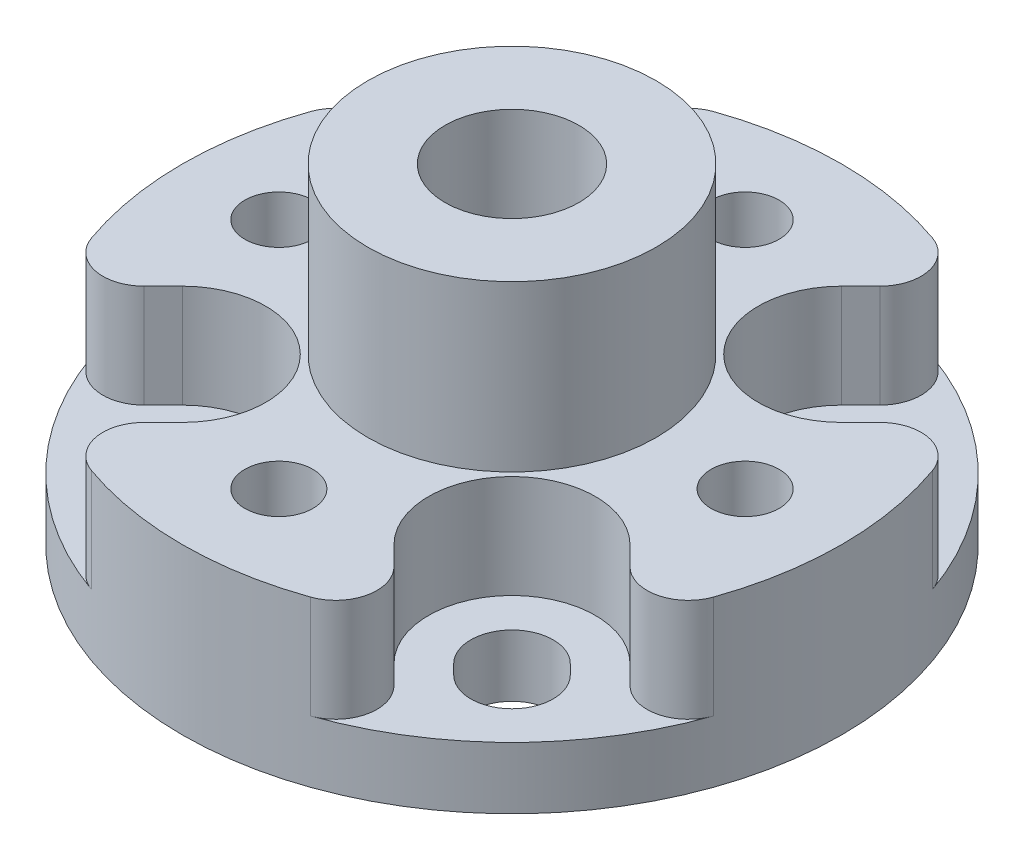
SolidWorks part; units mm, degrees
material "Brass"
ref_plane "前视基准面" through (0, 0, 0) normal (0, 0, 1) x (1, 0, 0)
ref_plane "上视基准面" through (0, 0, 0) normal (0, 1, 0) x (1, 0, 0)
ref_plane "右视基准面" through (0, 0, 0) normal (1, 0, 0) x (0, 0, -1)
sketch "Sketch1" plane through (0, 0, 0) normal (0, 1, 0) x (1, 0, 0)
  circle A0 centre (0, 0) radius 16
  dimension "D1" = 32
extrude "Boss-Extrude1" add sketch "Sketch1" along normal blind 8
sketch "Sketch2" plane through (0, 8, 0) normal (0, 1, 0) x (1, 0, 0)
  circle A0 centre (0, 0) radius 7
  dimension "D1" = 14
extrude "Boss-Extrude2" add sketch "Sketch2" along normal blind 8
sketch "Sketch3" plane through (0, 16, 0) normal (0, 1, 0) x (1, 0, 0)
  circle A0 centre (0, 0) radius 3.25
  dimension "D1" = 6.5
extrude "Cut-Extrude1" cut sketch "Sketch3" against normal through all
cosmetic thread "Cosmetic Thread1" parameters "D2"=8
sketch "Sketch4" plane through (0, 8, 0) normal (0, 1, 0) x (1, 0, 0)
  line L0 (-25.1061, 0) -> (26.0873, 0) construction
  line L1 (11.3137, 0) -> (0, 11.3137) construction
  line L2 (0, 11.3137) -> (-11.3137, 0) construction
  line L3 (-11.3137, 0) -> (0, -11.3137) construction
  line L4 (0, -11.3137) -> (11.3137, 0) construction
  circle A0 centre (0, 0) radius 8 construction
  circle A2 centre (0, 11.3137) radius 1.65
  circle A4 centre (-11.3137, 0) radius 1.65
  circle A5 centre (0, -11.3137) radius 1.65
  circle A6 centre (11.3137, 0) radius 1.65
  dimension "D1" = 16
  dimension "D2" = 3.3
  dimension "D3" = 3.3
  dimension "D4" = 3.3
  dimension "D5" = 3.3
extrude "Cut-Extrude2" cut sketch "Sketch4" against normal through all
cosmetic thread "Cosmetic Thread2" parameters "D2"=4
cosmetic thread "Cosmetic Thread3" parameters "D2"=4
cosmetic thread "Cosmetic Thread4" parameters "D2"=4
cosmetic thread "Cosmetic Thread5" parameters "D2"=4
sketch "Sketch5" plane through (0, 8, 0) normal (0, 1, 0) x (1, 0, 0)
  line L0 (0, 16.4633) -> (0, -18.0216) construction
  line L1 (-14.3574, 14.3574) -> (0, 0) construction
  line L2 (-8, 8) -> (-8.4853, 8.4853) construction
  line L7 (-9.4142, 6.5858) -> (-9.8995, 7.0711)
  line L8 (-6.5858, 9.4142) -> (-7.0711, 9.8995)
  line L9 (0, 0) -> (13.3651, 13.3651) construction
  line L10 (8, -8) -> (8.4853, -8.4853) construction
  line L11 (6.5858, -9.4142) -> (7.0711, -9.8995)
  line L12 (9.4142, -6.5858) -> (9.8995, -7.0711)
  line L13 (-23.0915, 0) -> (18.9541, 0) construction
  line L14 (8, 8) -> (8.4853, 8.4853) construction
  line L15 (6.5858, 9.4142) -> (7.0711, 9.8995)
  line L16 (9.4142, 6.5858) -> (9.8995, 7.0711)
  line L17 (-8, -8) -> (-8.4853, -8.4853) construction
  line L18 (-9.4142, -6.5858) -> (-9.8995, -7.0711)
  line L19 (-6.5858, -9.4142) -> (-7.0711, -9.8995)
  arc A0 (6.5858, 9.4142) -> (9.4142, 6.5858) centre (8, 8) ccw
  arc A1 (-9.4142, 6.5858) -> (-6.5858, 9.4142) centre (-8, 8) ccw
  arc A2 (-7.0711, 9.8995) -> (-9.8995, 7.0711) centre (-8.4853, 8.4853) ccw
  arc A3 (6.5858, -9.4142) -> (9.4142, -6.5858) centre (8, -8) cw
  arc A4 (9.8995, -7.0711) -> (7.0711, -9.8995) centre (8.4853, -8.4853) cw
  arc A5 (9.8995, 7.0711) -> (7.0711, 9.8995) centre (8.4853, 8.4853) ccw
  arc A6 (-9.4142, -6.5858) -> (-6.5858, -9.4142) centre (-8, -8) cw
  arc A7 (-7.0711, -9.8995) -> (-9.8995, -7.0711) centre (-8.4853, -8.4853) cw
  point P5 (-8.2426, 8.2426)
  point P18 (8.2426, -8.2426)
  point P25 (8.2426, 8.2426)
  point P34 (-8.2426, -8.2426)
  point P39 (0, 0)
  dimension "D2" = 8
  dimension "D3" = 2
  dimension "D1" = 45
  dimension "D4" = 90
  dimension "D5" = 24
  dimension "D6" = 2
extrude "Cut-Extrude3" cut sketch "Sketch5" against normal through all
sketch "Sketch6" plane through (0, 8, 0) normal (0, 1, 0) x (1, 0, 0)
  line L0 (0, 16.4633) -> (0, -18.1659) construction
  line L1 (-20.1715, 0) -> (22.2492, 0) construction
  line L2 (0, 0) -> (-13.628, 13.628) construction
  line L3 (-10.8638, 5.1362) -> (-11.7912, 6.0636)
  line L4 (5.1362, 10.8638) -> (6.0636, 11.7912)
  line L5 (-5.1362, 10.8638) -> (-6.0636, 11.7912)
  line L6 (10.8638, 5.1362) -> (11.7912, 6.0636)
  line L7 (10.8638, -5.1362) -> (11.7912, -6.0636)
  line L8 (5.1362, -10.8638) -> (6.0636, -11.7912)
  line L9 (-5.1362, -10.8638) -> (-6.0636, -11.7912)
  line L10 (-10.8638, -5.1362) -> (-11.7912, -6.0636)
  arc A0 (-10.8638, 5.1362) -> (-5.1362, 10.8638) centre (-8, 8) ccw
  arc A2 (-15.0919, 5.3136) -> (-11.7912, 6.0636) centre (-13.2054, 4.6494) cw
  arc A3 (-5.3136, 15.0919) -> (-6.0636, 11.7912) centre (-4.6494, 13.2054) ccw
  arc A5 (-5.3136, 15.0919) -> (-15.0919, 5.3136) centre (0, 0) ccw
  arc A6 (5.3136, 15.0919) -> (6.0636, 11.7912) centre (4.6494, 13.2054) cw
  arc A7 (5.1362, 10.8638) -> (10.8638, 5.1362) centre (8, 8) ccw
  arc A8 (15.0919, 5.3136) -> (11.7912, 6.0636) centre (13.2054, 4.6494) ccw
  arc A9 (15.0919, 5.3136) -> (5.3136, 15.0919) centre (0, 0) ccw
  arc A10 (15.0919, -5.3136) -> (11.7912, -6.0636) centre (13.2054, -4.6494) cw
  arc A11 (10.8638, -5.1362) -> (5.1362, -10.8638) centre (8, -8) ccw
  arc A12 (5.3136, -15.0919) -> (6.0636, -11.7912) centre (4.6494, -13.2054) ccw
  arc A13 (5.3136, -15.0919) -> (15.0919, -5.3136) centre (0, 0) ccw
  arc A14 (-5.3136, -15.0919) -> (-6.0636, -11.7912) centre (-4.6494, -13.2054) cw
  arc A15 (-5.1362, -10.8638) -> (-10.8638, -5.1362) centre (-8, -8) ccw
  arc A16 (-15.0919, -5.3136) -> (-11.7912, -6.0636) centre (-13.2054, -4.6494) ccw
  arc A17 (-15.0919, -5.3136) -> (-5.3136, -15.0919) centre (0, 0) ccw
  point P11 (2.8638, 2.8638)
  point P13 (-10.7642, 16.4918)
  point P14 (-2.8638, -2.8638)
  point P15 (-16.4918, 10.7642)
  point P52 (0, 0)
  dimension "D1" = 8.1
  dimension "D2" = 16
  dimension "D4" = 2
  dimension "D3" = 45
  dimension "D5" = 4.05
  dimension "D6" = 4.05
  dimension "D7" = 4
extrude "Cut-Extrude4" cut sketch "Sketch6" against normal blind 5 contours A2 L3 A0 L5 A3 A5 | L9 A14 A17 A16 L10 A15 | L7 A10 A13 A12 L8 A11 | L4 A6 A9 A8 L6 A7
